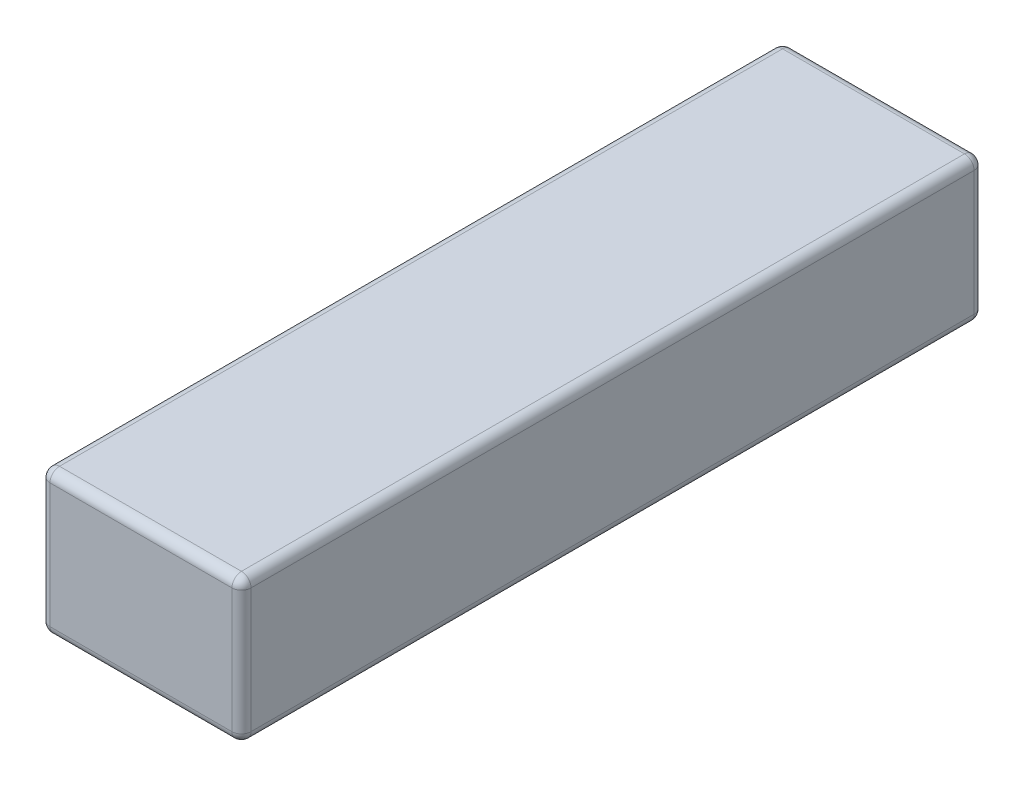
SolidWorks part; units mm, degrees
ref_plane "정면" through (0, 0, 0) normal (0, 0, 1) x (1, 0, 0)
ref_plane "윗면" through (0, 0, 0) normal (0, 1, 0) x (1, 0, 0)
ref_plane "우측면" through (0, 0, 0) normal (1, 0, 0) x (0, 0, -1)
sketch "스케치1" plane through (0, 0, 0) normal (0, 0, 1) x (1, 0, 0)
  line L1 (-31.8103, 17.1772) -> (10.1897, 17.1772)
  line L2 (-31.8103, 17.1772) -> (-31.8103, -12.8228)
  line L3 (-31.8103, -12.8228) -> (10.1897, -12.8228)
  line L4 (10.1897, 17.1772) -> (10.1897, -12.8228)
  line L5 (-31.8103, 17.1772) -> (10.1897, -12.8228) construction
  line L6 (-31.8103, -12.8228) -> (10.1897, 17.1772) construction
  point P0 (-10.8103, 2.1772)
  dimension "D1" = 42
  dimension "D2" = 30
extrude "보스-돌출1" add sketch "스케치1" along normal blind 155
fillet "필렛1" radius 2 12 edges at (-10.8103, -12.8228, 155) (-31.8103, 2.1772, 155) (-10.8103, 17.1772, 155) (10.1897, 2.1772, 155) (-10.8103, 17.1772, 0) (-31.8103, 2.1772, 0) (-10.8103, -12.8228, 0) (10.1897, 2.1772, 0) (-31.8103, -12.8228, 77.5) (-31.8103, 17.1772, 77.5) (10.1897, -12.8228, 77.5) (10.1897, 17.1772, 77.5)
